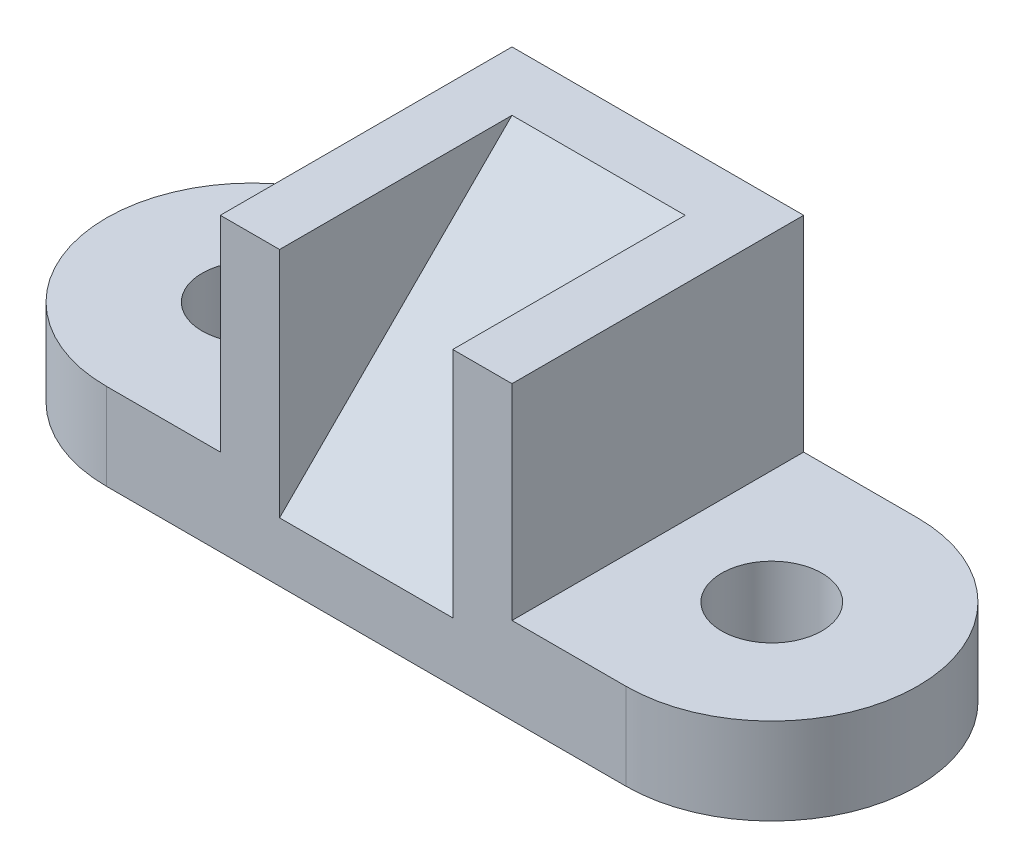
SolidWorks part; units mm, degrees
ref_plane "Front Plane" through (0, 0, 0) normal (0, 0, 1) x (1, 0, 0)
ref_plane "Top Plane" through (0, 0, 0) normal (0, 1, 0) x (1, 0, 0)
ref_plane "Right Plane" through (0, 0, 0) normal (1, 0, 0) x (0, 0, -1)
sketch "Sketch1" plane through (0, 0, 0) normal (0, 1, 0) x (1, 0, 0)
  line L0 (-57, 0) -> (57, 0) construction
  line L2 (-57, 32) -> (57, 32)
  line L3 (-57, -32) -> (57, -32)
  arc A0 (-57, 32) -> (-57, -32) centre (-57, 0) ccw
  arc A1 (57, -32) -> (57, 32) centre (57, 0) ccw
  circle A2 centre (-57, 0) radius 11
  circle A3 centre (57, 0) radius 11
  point P5 (0, 0)
  dimension "D2" = 32
  dimension "D3" = 22
  dimension "D4" = 22
  dimension "D1" = 114
extrude "Boss-Extrude1" add sketch "Sketch1" along normal blind 19
sketch "Sketch2" plane through (0, 19, 0) normal (0, 1, 0) x (1, 0, 0)
  line L1 (-32, -32) -> (32, -32)
  line L2 (-32, -32) -> (-32, 32)
  line L3 (-32, 32) -> (32, 32)
  line L4 (32, -32) -> (32, 32)
  line L5 (-32, -32) -> (32, 32) construction
  line L6 (-32, 32) -> (32, -32) construction
  point P0 (0, 0)
  dimension "D1" = 64
extrude "Boss-Extrude2" add sketch "Sketch2" along normal blind 45
sketch "Sketch3" plane through (-32, 0, 0) normal (-1, 0, 0) x (0, 0, 1)
  line L0 (32, 64) -> (-19, 64)
  line L1 (-32, 64) -> (32, 64) construction
  line L2 (-19, 64) -> (32, 13)
  line L3 (32, 19) -> (32, 0) construction
  line L4 (32, 13) -> (32, 64)
  dimension "D1" = 13
  dimension "D2" = 13
extrude "Cut-Extrude1" cut sketch "Sketch3" against normal blind 38 from offset 13
